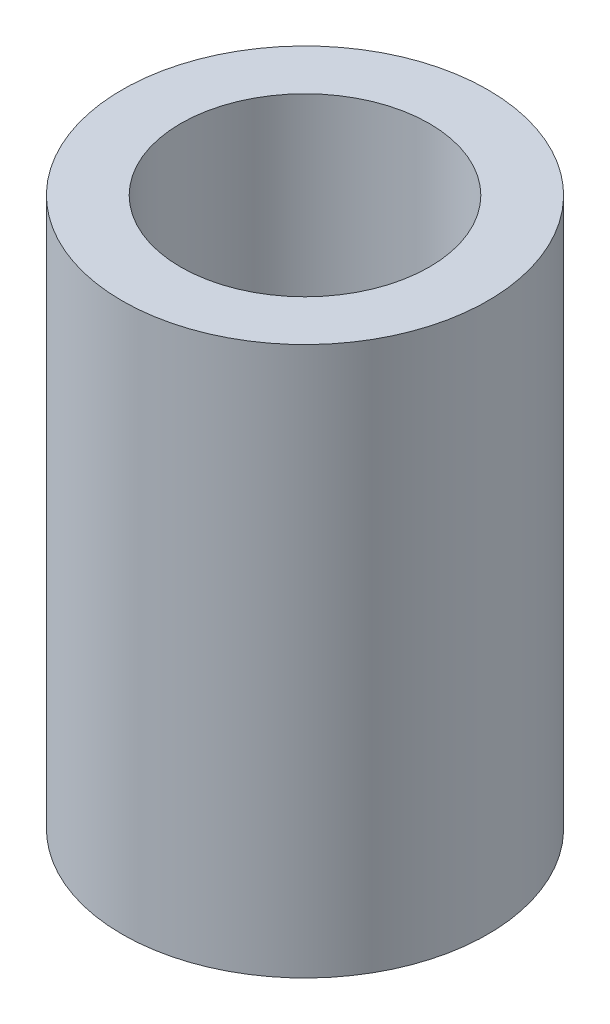
SolidWorks part; units mm, degrees
material "6061-T6 (SS)"
ref_plane "Front Plane" through (0, 0, 0) normal (0, 0, 1) x (1, 0, 0)
ref_plane "Top Plane" through (0, 0, 0) normal (0, 1, 0) x (1, 0, 0)
ref_plane "Right Plane" through (0, 0, 0) normal (1, 0, 0) x (0, 0, -1)
sketch "Sketch1" plane through (0, 0, 0) normal (0, 1, 0) x (1, 0, 0)
  circle A0 centre (0, 0) radius 4.7625
  circle A1 centre (0, 0) radius 3.2385
  dimension "D1" = 9.525
  dimension "D2" = 6.477
extrude "Boss-Extrude1" add sketch "Sketch1" along normal mid plane 14.2875
